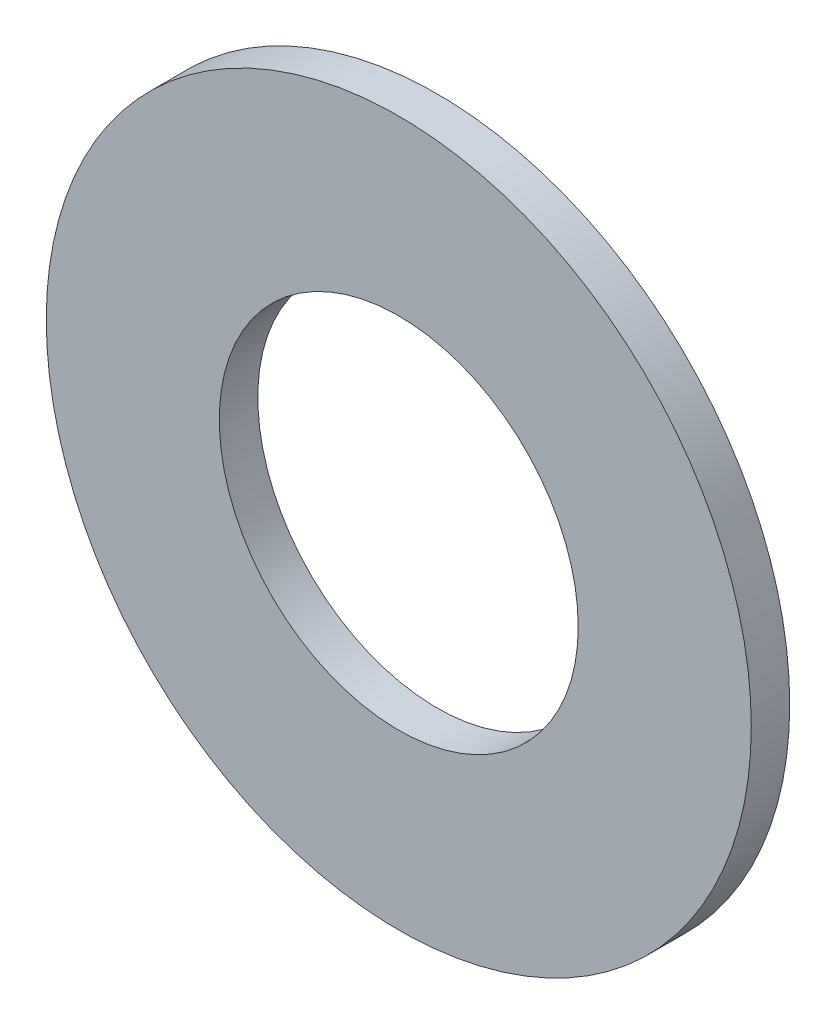
SolidWorks part; units mm, degrees
ref_plane "前视基准面" through (0, 0, 0) normal (0, 0, 1) x (1, 0, 0)
ref_plane "上视基准面" through (0, 0, 0) normal (0, 1, 0) x (1, 0, 0)
ref_plane "右视基准面" through (0, 0, 0) normal (1, 0, 0) x (0, 0, -1)
other "Configuration Table"
sketch "草图1" plane through (0, 0, 0) normal (0, 0, 1) x (1, 0, 0)
  circle A0 centre (0, 0) radius 14
  circle A1 centre (0, 0) radius 27.5
  dimension "D1" = 28
  dimension "D2" = 55
extrude "凸台-拉伸1" add sketch "草图1" along normal blind 3
sketch "草图2" plane through (0, 0, 3) normal (0, 0, 1) x (1, 0, 0)
  circle A0 centre (0, 0) radius 24 construction
  circle A1 centre (0, 24) radius 1.5
  dimension "D1" = 48
  dimension "D2" = 3
